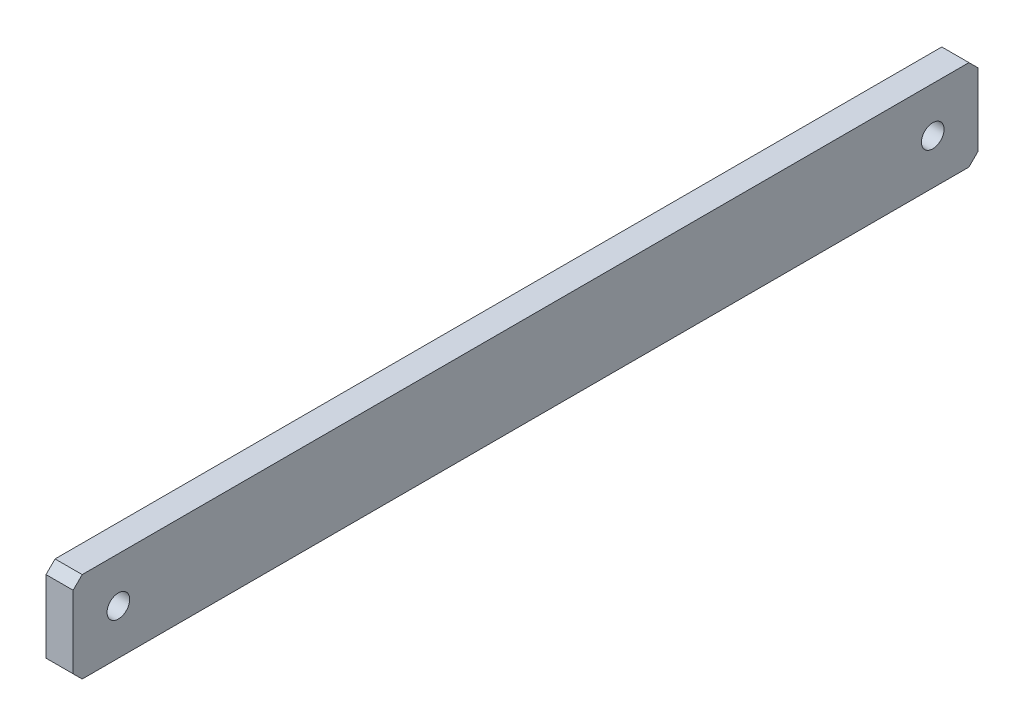
SolidWorks part; units mm, degrees
ref_plane "Front" through (0, 0, 0) normal (0, 0, 1) x (1, 0, 0)
ref_plane "Top" through (0, 0, 0) normal (0, 1, 0) x (1, 0, 0)
ref_plane "Right" through (0, 0, 0) normal (1, 0, 0) x (0, 0, -1)
sketch "草图1" plane through (0, 0, 0) normal (1, 0, 0) x (0, 0, -1)
  line L1 (50, -5) -> (-50, -5)
  line L2 (50, -5) -> (50, 5)
  line L3 (50, 5) -> (-50, 5)
  line L4 (-50, -5) -> (-50, 5)
  line L5 (50, -5) -> (-50, 5) construction
  line L6 (50, 5) -> (-50, -5) construction
  point P0 (0, 0)
  dimension "D1" = 100
  dimension "D2" = 10
extrude "凸台-拉伸1" add sketch "草图1" along normal blind 3
sketch "草图2" plane through (3, 0, 0) normal (1, 0, 0) x (0, 0, -1)
  line L0 (-50, 0) -> (50, 0) construction
  line L1 (-50, 5) -> (-50, -5) construction
  line L2 (50, -5) -> (50, 5) construction
  line L3 (0, 5) -> (0, -5) construction
  line L4 (50, 5) -> (-50, 5) construction
  line L5 (-50, -5) -> (50, -5) construction
  circle A0 centre (-45, 0) radius 1.25
  circle A1 centre (45, 0) radius 1.25
  point P16 (0, 0)
  dimension "D1" = 2.5
  dimension "D2" = 2.5
  dimension "D3" = 90
extrude "切除-拉伸1" cut sketch "草图2" against normal through all
chamfer "倒角1" distance 1 angle 45 4 edges at (1.5, -5, -50) (1.5, 5, -50) (1.5, -5, 50) (1.5, 5, 50)
